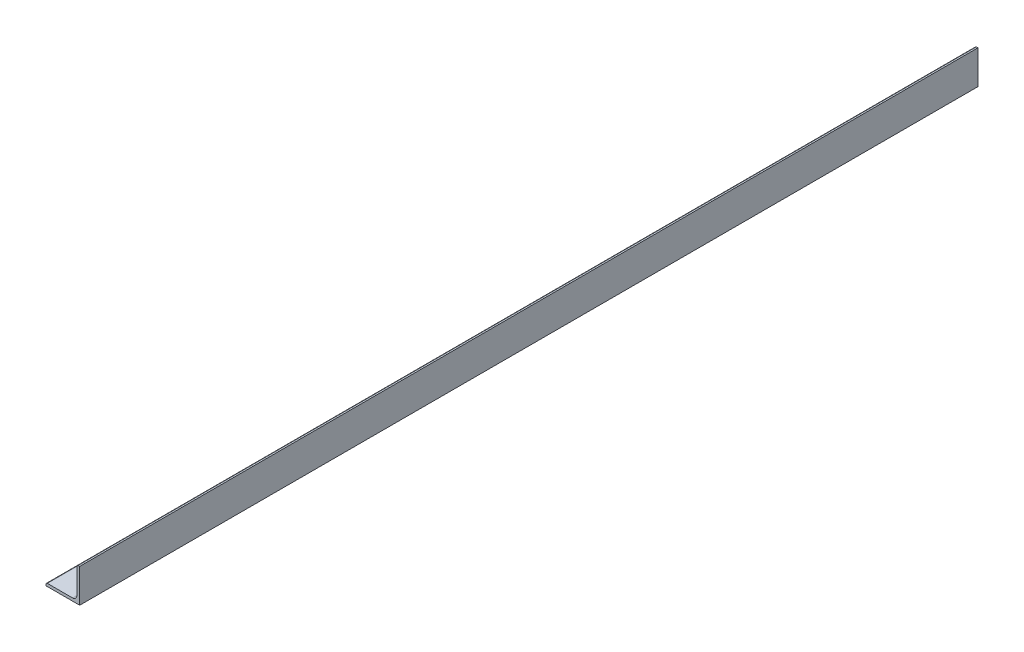
SolidWorks part; units mm, degrees
material "6061 Alloy"
ref_plane "Front Plane" through (0, 0, 0) normal (0, 0, 1) x (1, 0, 0)
ref_plane "Top Plane" through (0, 0, 0) normal (0, 1, 0) x (1, 0, 0)
ref_plane "Right Plane" through (0, 0, 0) normal (1, 0, 0) x (0, 0, -1)
sketch "Sketch0" plane through (0, 0, 0) normal (0, 0, 1) x (1, 0, 0)
  line L0 (-9.525, -9.525) -> (9.525, -9.525)
  line L1 (9.525, -9.525) -> (9.525, 9.525)
  line L2 (9.525, 0) -> (0, 0) construction
  line L3 (0, 0) -> (0, -9.525) construction
  line L4 (7.9375, -5.5499) -> (7.9375, 9.525) construction
  line L5 (5.5499, -7.9375) -> (-9.525, -7.9375) construction
  arc A0 (7.9375, -5.5499) -> (5.5499, -7.9375) centre (5.5499, -5.5499) cw
  point P3 (7.2382, -7.2382)
  dimension "Inside Corner Radius" = 2.3876
  dimension "Outside Height" = 19.05
  dimension "Inside Height" = 17.4625
  dimension "Inside Width" = 17.4625
  dimension "Wall Thickness" = 1.5875
  dimension "D1" = 1.5875
  dimension "Outside Width" = 19.05
sketch "Sketch1" plane through (0, 0, 0) normal (1, 0, 0) x (0, 0, -1)
  line L0 (254, 0) -> (-254, 0)
  point P4 (0, 0)
  dimension "Length" = 508
sketch "Sketch2" plane through (0, 0, 0) normal (0, 0, 1) x (1, 0, 0)
  line L0 (-9.525, -9.525) -> (9.525, -9.525)
  line L1 (9.525, -9.525) -> (9.525, 9.525)
  line L2 (9.525, 9.525) -> (7.9375, 9.525) construction
  line L3 (7.9375, 8.7313) -> (7.9375, -5.5499)
  line L4 (5.5499, -7.9375) -> (-8.7313, -7.9375)
  line L5 (-9.525, -9.525) -> (-9.525, -7.9375) construction
  line L6 (8.7313, 9.525) -> (9.525, 9.525)
  line L7 (-9.525, -8.7313) -> (-9.525, -9.525)
  line L8 (9.525, 0) -> (0, 0) construction
  line L9 (0, 0) -> (0, -9.525) construction
  arc A0 (7.9375, 8.7313) -> (8.7313, 9.525) centre (8.7313, 8.7313) cw
  arc A1 (-9.525, -8.7313) -> (-8.7313, -7.9375) centre (-8.7313, -8.7313) cw
  arc A2 (7.9375, -5.5499) -> (5.5499, -7.9375) centre (5.5499, -5.5499) cw
  dimension "Inside Radius" = 2.3876
  dimension "Height" = 19.05
  dimension "Width" = 19.05
  dimension "Thickness" = 1.5875
extrude "Boss-Extrude1" add sketch "Sketch2" along normal mid plane 508
sketch "Break Locations" plane through (0, 0, 0) normal (1, 0, 0) x (0, 0, -1)
  line L0 (-234.569, 0) -> (234.569, 0)
  line L1 (-254, -9.525) -> (-254, 9.525) construction
  line L2 (254, -9.525) -> (254, 9.525) construction
  point P0 (-237.8075, 0)
  point P1 (237.8075, 0)
  point P10 (0, 0)
  point P11 (234.569, 0)
  point P13 (-234.569, 0)
  dimension "D1" = 16.1925
  dimension "D2" = 16.1925
  dimension "D3" = 19.431
hole_wizard "#10 Clearance Hole1" positions "Sketch3" profile "Sketch4" hole size "#10" standard "ANSI Inch"
sketch "Sketch3" plane through (0, -9.525, 0) normal (0, -1, 0) x (-1, 0, 0)
  point P2 (-3.175, 241.3)
  point P5 (-3.175, 215.9)
  point P8 (-3.175, -241.3)
  point P11 (-3.175, -215.9)
sketch "Sketch4" plane through (3.175, -9.525, -241.3) normal (1, 0, 0) x (0, 0, -1)
  line L0 (0, 0) -> (0, 4.7977)
  line L1 (0, 4.7977) -> (2.4892, 3.302)
  line L2 (2.4892, 3.302) -> (2.4892, 0)
  line L5 (2.4892, 0) -> (0, 0)
  line L10 (0, 4.7977) -> (-2.4892, 3.302) construction
  line L11 (0, -6.35) -> (0, 107.95) construction
  dimension "Hole Dia." = 4.9784
  dimension "Hole Depth" = 3.302
  dimension "Drill Angle" = 118
equation "\"D1@Break Locations\" = .85 * \"Height@Sketch2\""
equation "\"D2@Break Locations\"=\"D1@Break Locations\""
equation "\"Thickness@Sketch2\"=\"wall thickness@sketch0\""
equation "\"Height@Sketch2\"=\"outside height@sketch0\""
equation "\"Width@Sketch2\"=\"outside width@sketch0\""
equation "\"Inside Radius@Sketch2\"=\"inside corner radius@sketch0\""
equation "\"Length@Boss-Extrude1\"=\"length@sketch1\""
equation "\"D3@Break Locations\"=\"D2@Break Locations\"*1.2"
equation "\"D1@Sketch0\"=\"Wall Thickness@Sketch0\""
